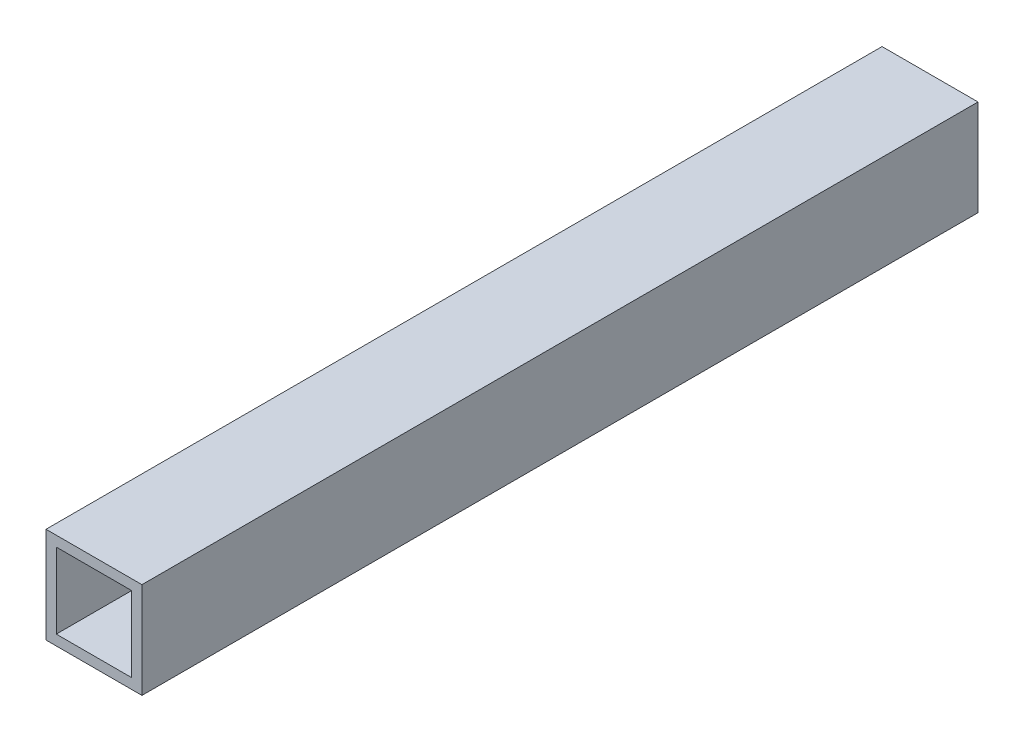
SolidWorks part; units mm, degrees
ref_plane "前视基准面" through (0, 0, 0) normal (0, 0, 1) x (1, 0, 0)
ref_plane "上视基准面" through (0, 0, 0) normal (0, 1, 0) x (1, 0, 0)
ref_plane "右视基准面" through (0, 0, 0) normal (1, 0, 0) x (0, 0, -1)
sketch "草图1" plane through (0, 0, 0) normal (0, 0, 1) x (1, 0, 0)
  line L1 (-5.5, 5.5) -> (5.5, 5.5)
  line L2 (-5.5, 5.5) -> (-5.5, -5.5)
  line L3 (-5.5, -5.5) -> (5.5, -5.5)
  line L4 (5.5, 5.5) -> (5.5, -5.5)
  line L5 (-5.5, 5.5) -> (5.5, -5.5) construction
  line L6 (-5.5, -5.5) -> (5.5, 5.5) construction
  point P0 (0, 0)
  dimension "D1" = 11
extrude "拉伸-薄壁1" add sketch "草图1" along normal blind 122 thin thin type one direction wall 1.5
